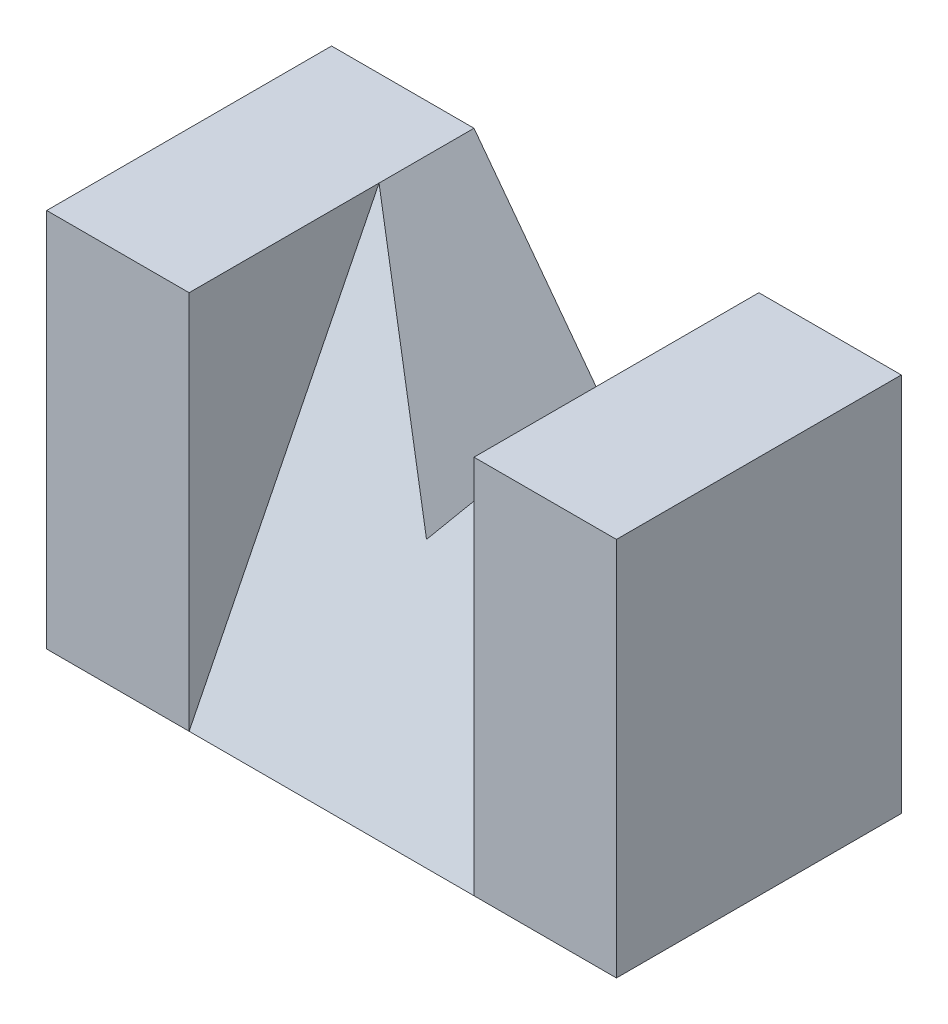
SolidWorks part; units mm, degrees
ref_plane "前基準面" through (0, 0, 0) normal (0, 0, 1) x (1, 0, 0)
ref_plane "上基準面" through (0, 0, 0) normal (0, 1, 0) x (1, 0, 0)
ref_plane "右基準面" through (0, 0, 0) normal (1, 0, 0) x (0, 0, -1)
sketch "草圖1" plane through (0, 0, 0) normal (0, 1, 0) x (1, 0, 0)
  line L1 (-30, 0) -> (30, 0)
  line L2 (-30, 0) -> (-30, 30)
  line L3 (-30, 30) -> (30, 30)
  line L4 (30, 0) -> (30, 30)
  point P7 (0, 0)
  dimension "D1" = 30
  dimension "D2" = 60
extrude "填料-伸長1" add sketch "草圖1" along normal blind 40
sketch "草圖3" plane through (0, 0, 0) normal (0, 0, 1) x (1, 0, 0)
  line L0 (-15, 40) -> (0, 20)
  line L1 (-30, 40) -> (30, 40) construction
  line L2 (0, 20) -> (15, 40)
  line L3 (15, 40) -> (-15, 40)
  line L4 (0, 20) -> (0, 47.41) construction
  point P4 (0, 40)
  point P8 (0, 40)
  dimension "D1" = 30
  dimension "D2" = 20
extrude "除料-伸長1" cut sketch "草圖3" against normal through all
sketch "草圖4" plane through (0, 0, 0) normal (1, 0, 0) x (0, 0, -1)
  line L0 (0, 40) -> (20, 40)
  line L1 (0, 40) -> (30, 40) construction
  line L2 (20, 40) -> (0, 0)
  line L3 (0, 0) -> (0, 40)
  dimension "D1" = 20
extrude "除料-伸長2" cut sketch "草圖4" against normal mid plane 30
